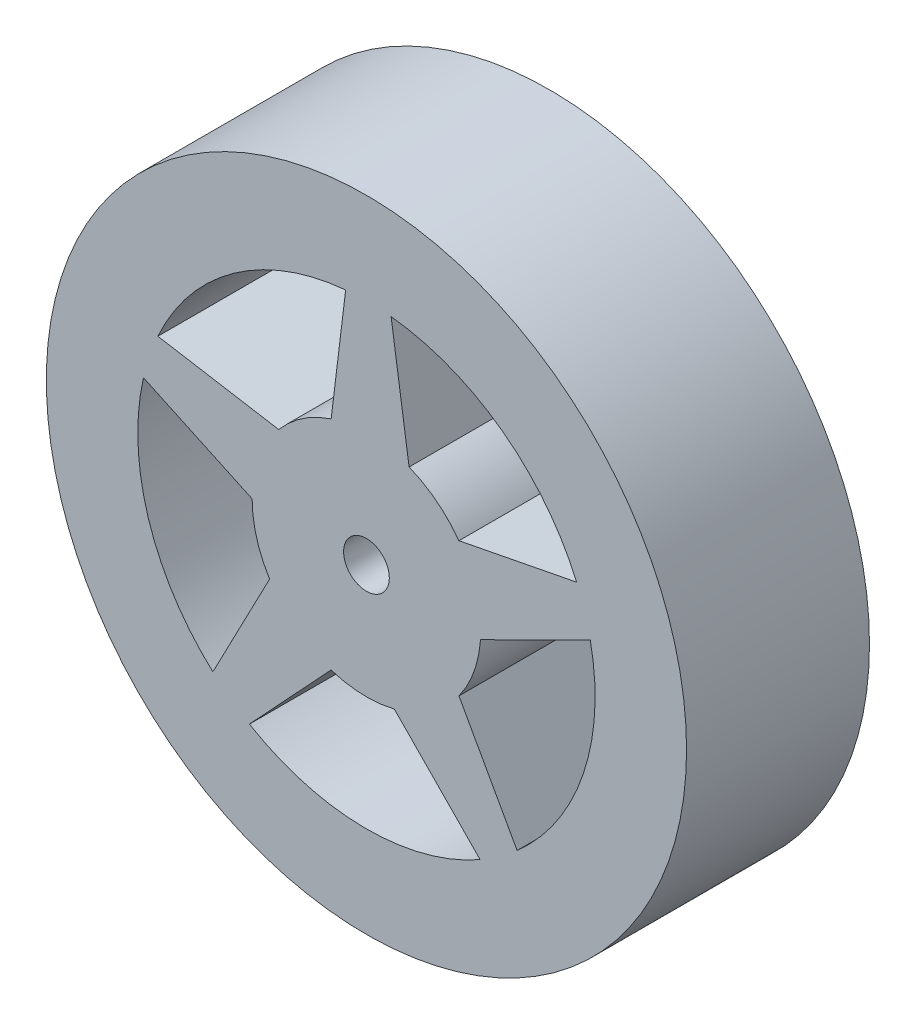
SolidWorks part; units mm, degrees
ref_plane "前视基准面" through (0, 0, 0) normal (0, 0, 1) x (1, 0, 0)
ref_plane "上视基准面" through (0, 0, 0) normal (0, 1, 0) x (1, 0, 0)
ref_plane "右视基准面" through (0, 0, 0) normal (1, 0, 0) x (0, 0, -1)
sketch "草图1" plane through (0, 0, 0) normal (0, 0, 1) x (1, 0, 0)
  circle A0 centre (0, 0) radius 35
  circle A1 centre (0, 0) radius 25
  dimension "D1" = 70
  dimension "D2" = 50
extrude "凸台-拉伸1" add sketch "草图1" along normal mid plane 20
sketch "草图2" plane through (0, 0, 0) normal (0, 0, 1) x (1, 0, 0)
  line L0 (-3.8594, 11.8893) -> (-1.4388, 31.7128)
  line L1 (-1.4388, 31.7128) -> (1.6786, 31.7128)
  line L2 (1.6786, 31.7128) -> (4.6625, 11.5979)
  circle A0 centre (0, 0) radius 12.5
  dimension "D1" = 25
extrude "凸台-拉伸2" add sketch "草图2" along normal mid plane 20 contours A0 | A0 L2 L1 L0
pattern_circular "阵列(圆周)1" count 5 over 360 about axis through (0, 0, 0) along (0, 0, 1) of "凸台-拉伸2"
sketch "草图3" plane through (0, 0, 10) normal (0, 0, 1) x (1, 0, 0)
  circle A0 centre (0, 0) radius 2.5
  dimension "D1" = 5
extrude "切除-拉伸1" cut sketch "草图3" against normal through all
